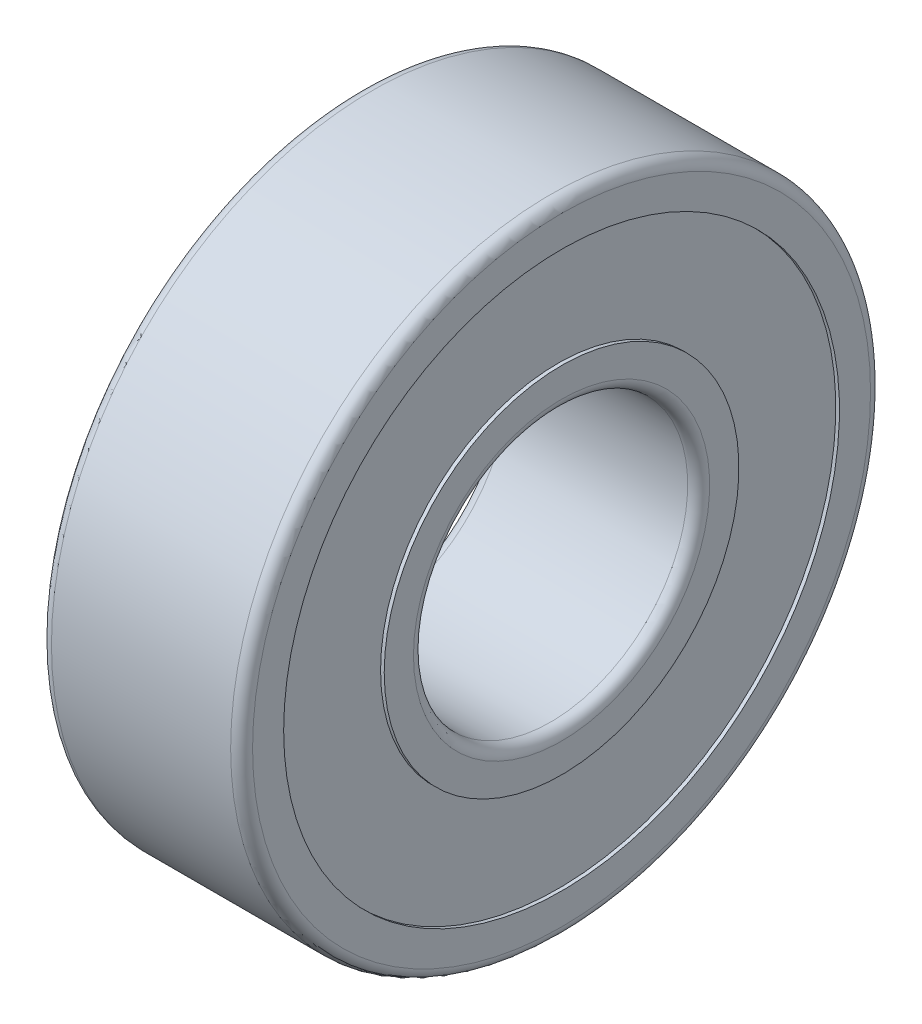
SolidWorks part; units mm, degrees
material "Plain Carbon Steel"
ref_plane "Front Plane" through (0, 0, 0) normal (0, 0, 1) x (1, 0, 0)
ref_plane "Top Plane" through (0, 0, 0) normal (0, 1, 0) x (1, 0, 0)
ref_plane "Right Plane" through (0, 0, 0) normal (1, 0, 0) x (0, 0, -1)
sketch "Sketch1" plane through (0, 0, 0) normal (0, 0, 1) x (1, 0, 0)
  line L0 (0, 0) -> (8.8933, 0) construction
  line L1 (0, 9.7) -> (0, 7.5)
  line L2 (0, 7.5) -> (11, 7.5)
  line L3 (11, 7.5) -> (11, 9.7)
  line L4 (11, 9.7) -> (10.8, 9.7)
  line L5 (10.8, 9.7) -> (10.8, 15.2)
  line L6 (10.8, 15.2) -> (11, 15.2)
  line L7 (11, 15.2) -> (11, 17.5)
  line L8 (11, 17.5) -> (0, 17.5)
  line L9 (0, 17.5) -> (0, 15.2)
  line L10 (0, 15.2) -> (0.2, 15.2)
  line L11 (0.2, 15.2) -> (0.2, 9.7)
  line L12 (0.2, 9.7) -> (0, 9.7)
  dimension "D1" = 15
  dimension "D2" = 35
  dimension "D3" = 30.4
  dimension "D4" = 19.4
  dimension "D5" = 0.2
  dimension "D6" = 11
revolve "Revolve1" add sketch "Sketch1" angle 360 about L0
fillet "Fillet1" radius 0.6 4 edges at (0, 0, 7.5) (11, 0, 7.5) (11, 0, 17.5) (0, 0, 17.5)
